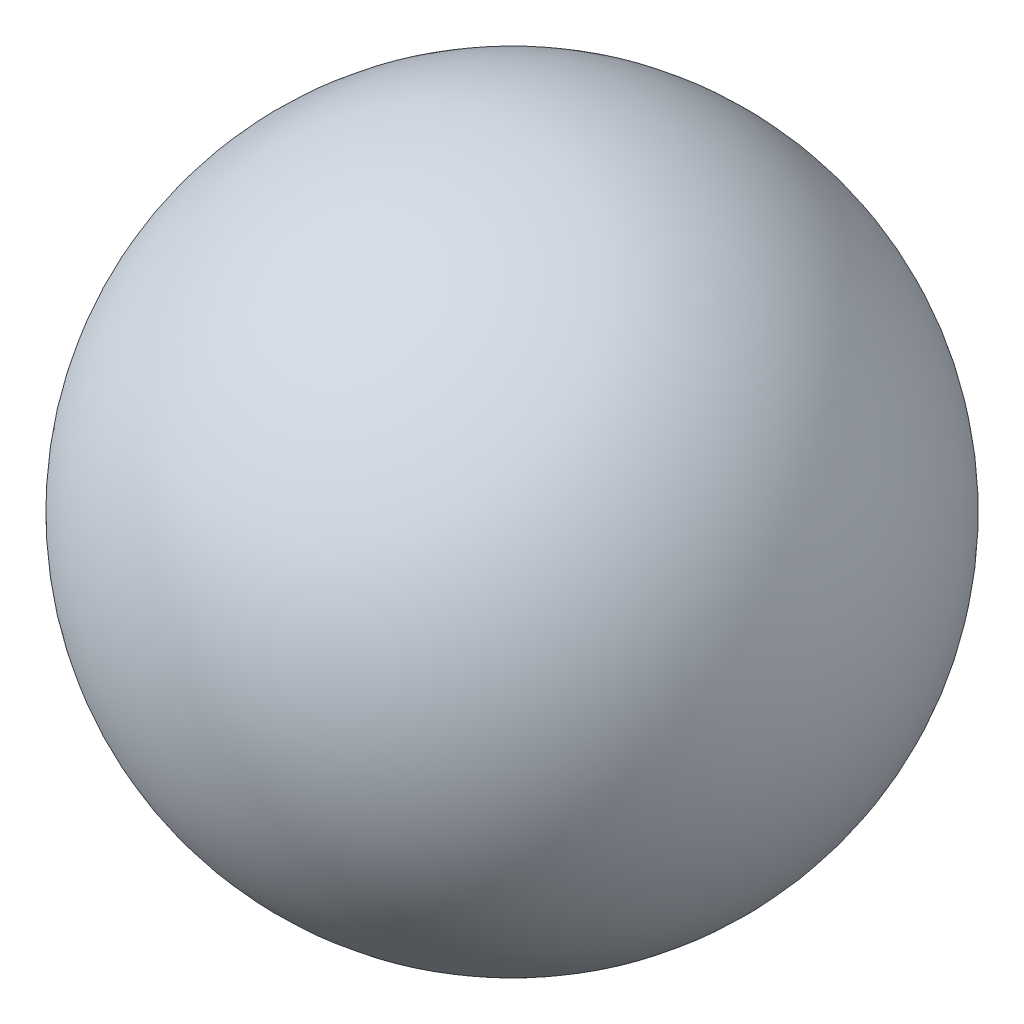
SolidWorks part; units mm, degrees
ref_plane "前视基准面" through (0, 0, 0) normal (0, 0, 1) x (1, 0, 0)
ref_plane "上视基准面" through (0, 0, 0) normal (0, 1, 0) x (1, 0, 0)
ref_plane "右视基准面" through (0, 0, 0) normal (1, 0, 0) x (0, 0, -1)
sketch "草图1" plane through (0, 0, 0) normal (0, 0, 1) x (1, 0, 0)
  line L0 (0, 115) -> (0, -115)
  arc A0 (0, 115) -> (0, -115) centre (0, 0) ccw
  dimension "D1" = 230
revolve "旋转1" add sketch "草图1" angle 360 about L0
ref_point "点1"
sketch3d "URDF Reference"
  line L0 (0, 0, 0) -> (10, 0, 0) construction
  line L1 (0, 0, 0) -> (0, 0, -10) construction
  point P0 (0, 0, 0)
  point P1 (0, 0, 0)
